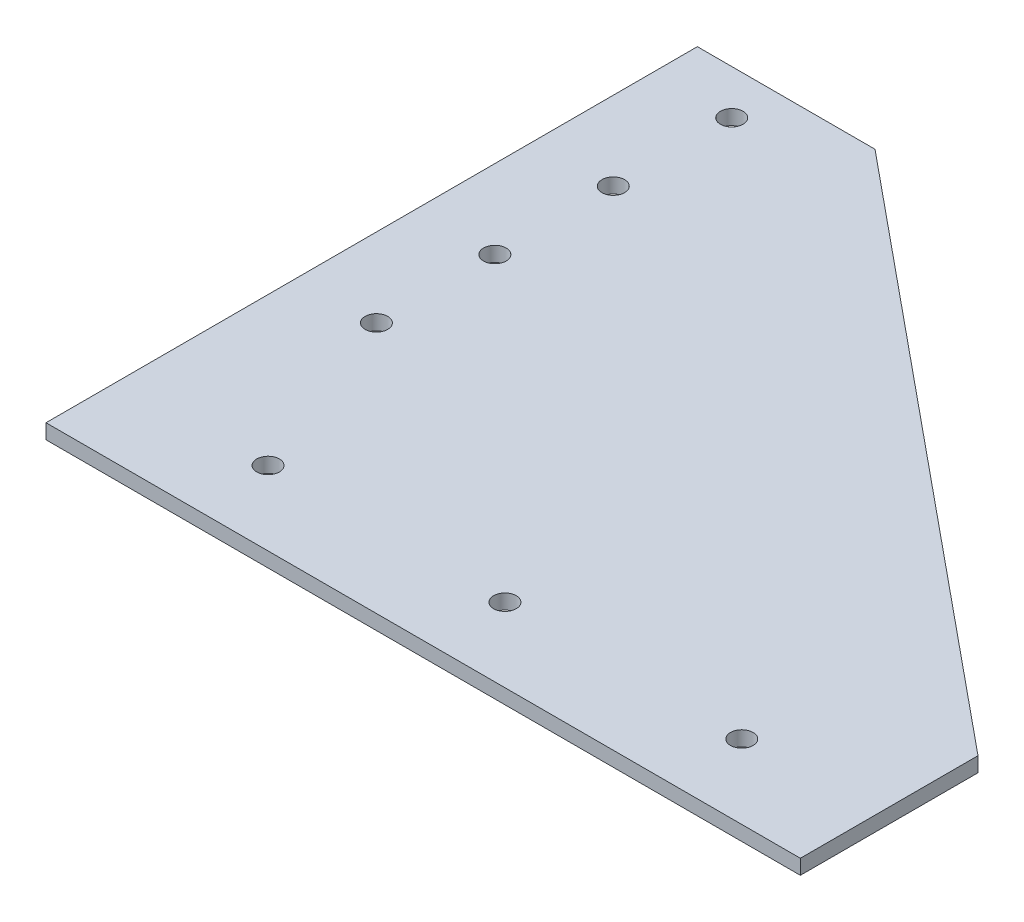
SolidWorks part; units mm, degrees
material "5052-H32"
ref_plane "Front" through (0, 0, 0) normal (0, 0, 1) x (1, 0, 0)
ref_plane "Top" through (0, 0, 0) normal (0, 1, 0) x (1, 0, 0)
ref_plane "Right" through (0, 0, 0) normal (1, 0, 0) x (0, 0, -1)
sketch "Sketch1" plane through (0, 0, 0) normal (0, 1, 0) x (1, 0, 0)
  line L0 (0, 0) -> (0, 139.7)
  line L1 (0, 139.7) -> (38.1, 139.7)
  line L2 (38.1, 139.7) -> (161.7899, 38.1)
  line L3 (0, 0) -> (161.7899, 0)
  line L4 (161.7899, 0) -> (161.7899, 38.1)
  circle A0 centre (31.75, 15.875) radius 2.4257
  circle A1 centre (82.55, 15.875) radius 2.4257
  circle A2 centre (133.35, 15.875) radius 2.4257
  circle A3 centre (16.891, 53.975) radius 2.4257
  circle A4 centre (16.891, 79.375) radius 2.4257
  circle A5 centre (16.891, 104.775) radius 2.4257
  circle A6 centre (16.891, 130.175) radius 2.4257
  dimension "D1" = 4.8514
  dimension "D2" = 139.7
  dimension "D3" = 38.1
  dimension "D4" = 39.4
  dimension "D5" = 15.875
  dimension "D6" = 31.75
  dimension "D8" = 38.1
  dimension "D9" = 50.8
  dimension "D10" = 16.891
  dimension "D11" = 53.975
  dimension "D13" = 25.4
  dimension "D7" = 3
  dimension "D12" = 4
extrude "Boss-Extrude1" add sketch "Sketch1" along normal blind 3.175
fillet "Fillet1" [suppressed] radius 3.175
sketch "Sketch2" plane through (0, 3.175, 0) normal (0, 1, 0) x (1, 0, 0)
  line L0 (0, 0) -> (161.7899, 0) construction
  line L1 (0, 139.7) -> (0, 0) construction
  circle A0 centre (63.5, 63.5) radius 4.3688
  dimension "D1" = 8.7376
  dimension "D2" = 63.5
  dimension "D3" = 63.5
extrude "Cut-Extrude1" [suppressed] cut sketch "Sketch2" against normal through all
